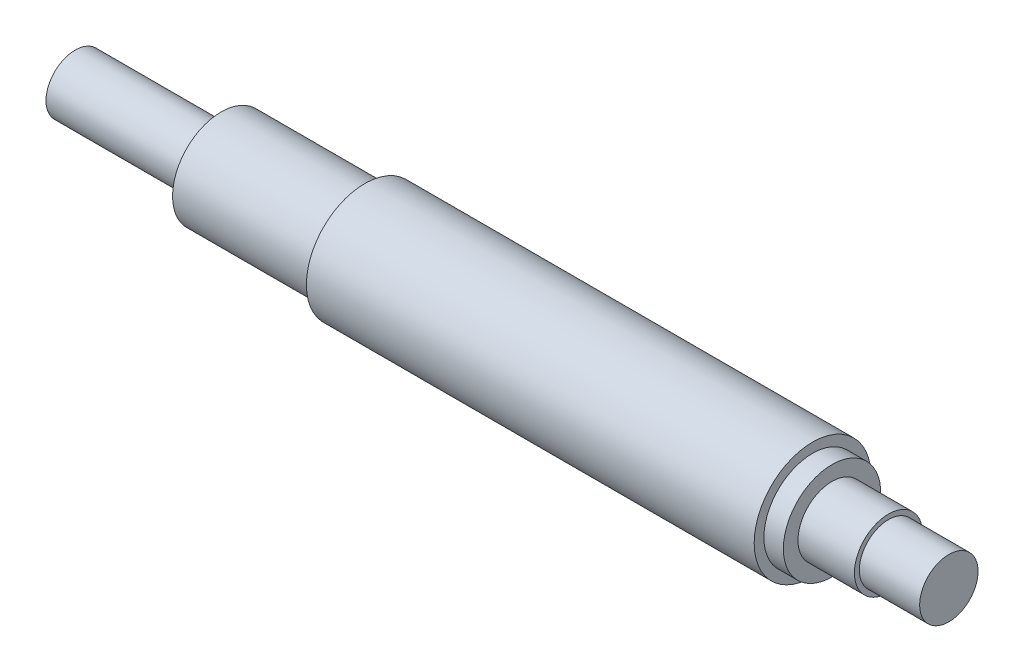
SolidWorks part; units mm, degrees
material "Alloy Steel"
ref_plane "Front Plane" through (0, 0, 0) normal (0, 0, 1) x (1, 0, 0)
ref_plane "Top Plane" through (0, 0, 0) normal (0, 1, 0) x (1, 0, 0)
ref_plane "Right Plane" through (0, 0, 0) normal (1, 0, 0) x (0, 0, -1)
sketch "Sketch2" plane through (0, 0, 0) normal (0, 0, 1) x (1, 0, 0)
  line L0 (-42.375, 0) -> (42.375, 0)
  line L1 (-42.375, 0) -> (-42.375, 3)
  line L2 (-42.375, 3) -> (-32.375, 3)
  line L3 (-17.625, 5) -> (-17.625, 6)
  line L4 (-17.625, 6) -> (28.375, 6)
  line L5 (28.375, 6) -> (28.375, 5)
  line L6 (-32.375, 3) -> (-32.375, 5)
  line L7 (-32.375, 5) -> (-17.625, 5)
  line L8 (28.375, 5) -> (30.375, 5)
  line L9 (30.375, 5) -> (30.375, 3.5)
  line L10 (30.375, 3.5) -> (36.175, 3.5)
  line L11 (36.175, 3.5) -> (36.175, 3)
  line L13 (36.175, 3) -> (42.375, 3)
  line L14 (42.375, 3) -> (42.375, 0)
  point P5 (0, 0)
  dimension "D2" = 6
  dimension "D3" = 3
  dimension "D4" = 10
  dimension "D5" = 24.75
  dimension "D6" = 46
  dimension "D7" = 5.8
  dimension "D8" = 2
  dimension "D9" = 5
  dimension "D11" = 5
  dimension "D12" = 6.2
  dimension "D10" = 3.5
  dimension "D13" = 3
revolve "Revolve1" add sketch "Sketch2" angle 360 about L0
sketch "Sketch3" [suppressed] plane through (0, 0, 0) normal (0, 0, 1) x (1, 0, 0)
  line L0 (-43.375, 0) -> (43.375, 0)
  line L1 (-43.375, 0) -> (-43.375, 3)
  line L2 (-43.375, 3) -> (-33.375, 3)
  line L3 (-20.625, 5) -> (-20.625, 7.5)
  line L4 (-20.625, 7.5) -> (29.375, 7.5)
  line L5 (29.375, 7.5) -> (29.375, 5)
  line L6 (-33.375, 3) -> (-33.375, 5)
  line L7 (-33.375, 5) -> (-20.625, 5)
  line L8 (29.375, 5) -> (31.375, 5)
  line L9 (31.375, 5) -> (31.375, 3.5)
  line L10 (31.375, 3.5) -> (37.175, 3.5)
  line L11 (43.375, 3) -> (43.375, 0)
  line L13 (4.375, 7.5) -> (4.375, 16.7852) construction
  line L14 (37.175, 3.5) -> (37.175, 3)
  line L15 (37.175, 3) -> (43.375, 3)
  point P4 (0, 0)
  point P17 (29.375, 6.25)
  dimension "D12" = 6.2
  dimension "D2" = 7.5
  dimension "D4" = 3
  dimension "D1" = 10
  dimension "D8" = 5
  dimension "D10" = 5
  dimension "D3" = 50
  dimension "D5" = 22.75
  dimension "D7" = 2
  dimension "D6" = 3.5
  dimension "D9" = 3
  dimension "D11" = 5.8
revolve "Revolve2" [suppressed] add sketch "Sketch3" angle 360 about L0
sketch "Sketch5" [suppressed] plane through (-43.375, 0, 0) normal (-1, 0, 0) x (0, 0, 1)
  circle A1 centre (0, 0) radius 3
  circle A2 centre (0, 0) radius 3
  dimension "D1" = 0
extrude "Boss-Extrude1" [suppressed] add sketch "Sketch5" along normal blind 5
sketch "Sketch6" plane through (-42.375, 0, 0) normal (-1, 0, 0) x (0, 0, 1)
  circle A1 centre (0, 0) radius 3
  circle A2 centre (0, 0) radius 3
  dimension "D1" = 0
extrude "Boss-Extrude2" add sketch "Sketch6" along normal blind 5
equation "\"mini-flipper-shaft-diameter\"= 26mm"
equation "\"mini-shaft-ring-groove-diam\"= 7.8mm"
equation "\"mini-shaft-ring-groove-width\"= 1mm"
equation "\"dtCoverPlate-DistFrom-GearCent\"= 73mm"
equation "\"wormGearShaft-L\"= \"dtCoverPlate-DistFrom-GearCent\" - 27.75 + 3.75"
equation "\"wormGearShaft-Dsmall\"= 6mm"
equation "\"wormGearShaft-Dworm\"= 12mm"
equation "\"D3@Sketch2\"=\"wormGearShaft-Dsmall\"/2"
equation "\"D4@Sketch3\"=\"wormGearShaft-Dsmall\"/2"
equation "\"wormL-D\" = 12mm"
equation "\"wormR-D\" = 15mm"
equation "\"wormGearL-D\" = 46mm"
equation "\"wormGearR-D\" = 50mm"
equation "\"D5@Sketch3\"=73-\"wormGearR-D\"/2 - 17.25-8"
equation "\"D5@Sketch2\"=73-\"wormGearL-D\"/2 -17.25-8"
equation "\"D2@Sketch2\"=\"wormL-D\"/2"
equation "\"D6@Sketch2\"=\"wormGearL-D\""
